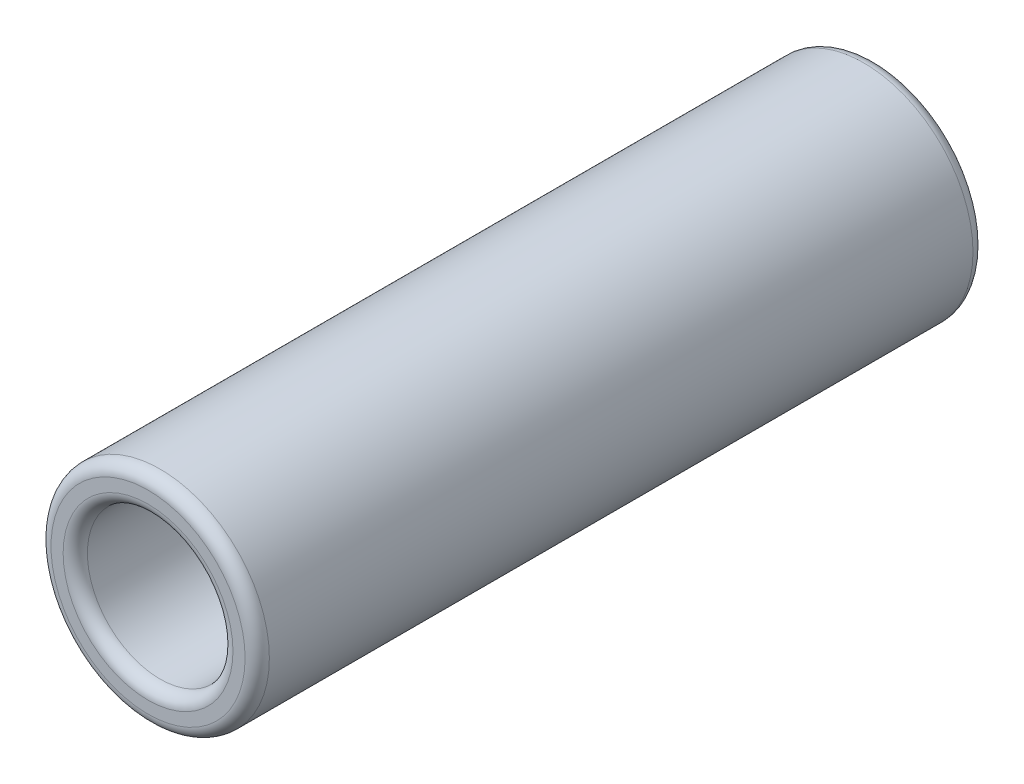
SolidWorks part; units mm, degrees
ref_plane "Front Plane" through (0, 0, 0) normal (0, 0, 1) x (1, 0, 0)
ref_plane "Top Plane" through (0, 0, 0) normal (0, 1, 0) x (1, 0, 0)
ref_plane "Right Plane" through (0, 0, 0) normal (1, 0, 0) x (0, 0, -1)
sketch "Sketch1" plane through (0, 0, 0) normal (0, 0, 1) x (1, 0, 0)
  circle A0 centre (0, 0) radius 3
  circle A1 centre (0, 0) radius 4.5
  dimension "D1" = 6
  dimension "D2" = 9
extrude "Boss-Extrude1" add sketch "Sketch1" along normal mid plane 30
fillet "Fillet1" radius 0.5 4 edges at (4.5, 0, -15) (3, 0, -15) (3, 0, 15) (4.5, 0, 15)
